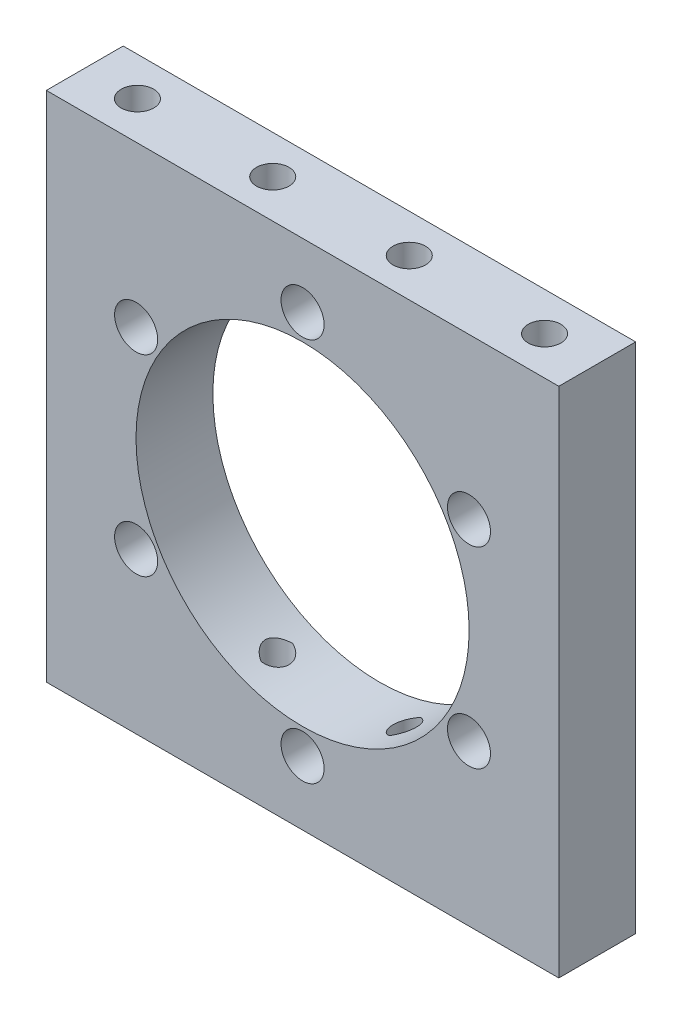
SolidWorks part; units mm, degrees
ref_plane "Front Plane" through (0, 0, 0) normal (0, 0, 1) x (1, 0, 0)
ref_plane "Top Plane" through (0, 0, 0) normal (0, 1, 0) x (1, 0, 0)
ref_plane "Right Plane" through (0, 0, 0) normal (1, 0, 0) x (0, 0, -1)
ref_plane "Plane1" through (0, 0, 0) normal (0, 0, -1) x (-1, 0, 0)
sketch "Sketch1" plane through (0, 0, 0) normal (0, 0, -1) x (-1, 0, 0)
  line L0 (-31.75, 31.75) -> (-31.75, -31.75)
  line L1 (-31.75, -31.75) -> (31.75, -31.75)
  line L2 (31.75, -31.75) -> (31.75, 31.75)
  line L3 (31.75, 31.75) -> (-31.75, 31.75)
extrude "Boss-Extrude1" add sketch "Sketch1" against normal blind 9.525
sketch "Sketch2" plane through (0, 0, 9.525) normal (0, 0, 1) x (1, 0, 0)
  circle A0 centre (0, 0) radius 20.6375
  dimension "D1" = 41.275
extrude "Cut-Extrude1" cut sketch "Sketch2" against normal through all
hole_wizard "#10-32 Tapped Hole1" positions "Sketch4" profile "Sketch3" tap size "#10-32" standard "ANSI Inch"
sketch "Sketch4" plane through (0, -31.75, 0) normal (0, -1, 0) x (-1, 0, 0)
  line L0 (-31.75, 0) -> (31.75, 0) construction
  line L1 (31.75, -4.7625) -> (-31.75, -4.7625) construction
  line L2 (31.75, -9.525) -> (31.75, 0) construction
  line L3 (-31.75, -9.525) -> (-31.75, 0) construction
  point P0 (-8.4582, -4.7625)
  point P1 (8.4582, -4.7625)
  point P5 (0, 0)
  point P16 (25.2222, -4.7625)
  point P18 (-25.2222, -4.7625)
  dimension "D1" = 8.4582
  dimension "D2" = 8.4582
  dimension "D3" = 16.764
  dimension "D4" = 16.764
sketch "Sketch3" plane through (8.4582, -31.75, 4.7625) normal (1, 0, 0) x (0, 0, -1)
  line L0 (0, 0) -> (0, 13.9133)
  line L1 (0, 13.9133) -> (2.0193, 12.7)
  line L2 (2.0193, 12.7) -> (2.0193, 0)
  line L5 (2.0193, 0) -> (0, 0)
  line L10 (0, 13.9133) -> (-2.0193, 12.7) construction
  line L11 (0, -6.35) -> (0, 107.95) construction
  dimension "Tap Drill Dia." = 4.0386
  dimension "Tap Drill Depth" = 12.7
  dimension "Drill Angle" = 118
hole_wizard "#10 (0.1935) Diameter Hole1" positions "Sketch8" profile "Sketch7" hole size "#10" standard "ANSI Inch" end condition through all
sketch "Sketch8" plane through (0, 0, 0) normal (0, 0, -1) x (-1, 0, 0)
  line L1 (0, 23.8125) -> (-20.6222, 11.9062) construction
  line L2 (-20.6222, 11.9062) -> (-20.6222, -11.9063) construction
  line L3 (-20.6222, -11.9063) -> (0, -23.8125) construction
  line L4 (0, -23.8125) -> (20.6222, -11.9062) construction
  line L5 (20.6222, -11.9062) -> (20.6222, 11.9063) construction
  line L6 (20.6222, 11.9063) -> (0, 23.8125) construction
  circle A0 centre (0, 0) radius 23.8125 construction
  circle A1 centre (0, 0) radius 20.6222 construction
  point P0 (-20.6222, 11.9062)
  point P1 (-20.6222, -11.9063)
  point P2 (0, -23.8125)
  point P3 (20.6222, -11.9062)
  point P4 (20.6222, 11.9063)
  point P5 (0, 23.8125)
  point P20 (0, 23.8125)
  point P21 (20.6222, 11.9063)
  point P22 (20.6222, -11.9062)
  point P23 (0, -23.8125)
  point P24 (-20.6222, -11.9063)
  point P25 (-20.6222, 11.9062)
  dimension "D1" = 47.625
sketch "Sketch7" plane through (20.6222, 11.9062, 0) normal (1, 0, 0) x (0, 1, 0)
  line L0 (0, 0) -> (0, 9.525)
  line L1 (0, 9.525) -> (2.667, 9.525)
  line L2 (2.667, 9.525) -> (2.667, 0)
  line L5 (2.667, 0) -> (0, 0)
  line L11 (0, -6.35) -> (0, 107.95) construction
  dimension "Thru Hole Dia." = 5.334
  dimension "Thru Hole Depth" = 9.525
sketch "Sketch9" plane through (0, 0, 9.525) normal (0, 0, 1) x (1, 0, 0)
  circle A0 centre (0, 0) radius 20.6375
  circle A1 centre (0, 0) radius 17.4625
  circle A3 centre (0, 0) radius 20.6375 construction
  dimension "D1" = 34.925
extrude "Boss-Extrude2" [suppressed] add sketch "Sketch9" against normal blind 3.175
mirror "Mirror1" about plane through (0, 0, 0) normal (0, 1, 0) of "#10-32 Tapped Hole1"
